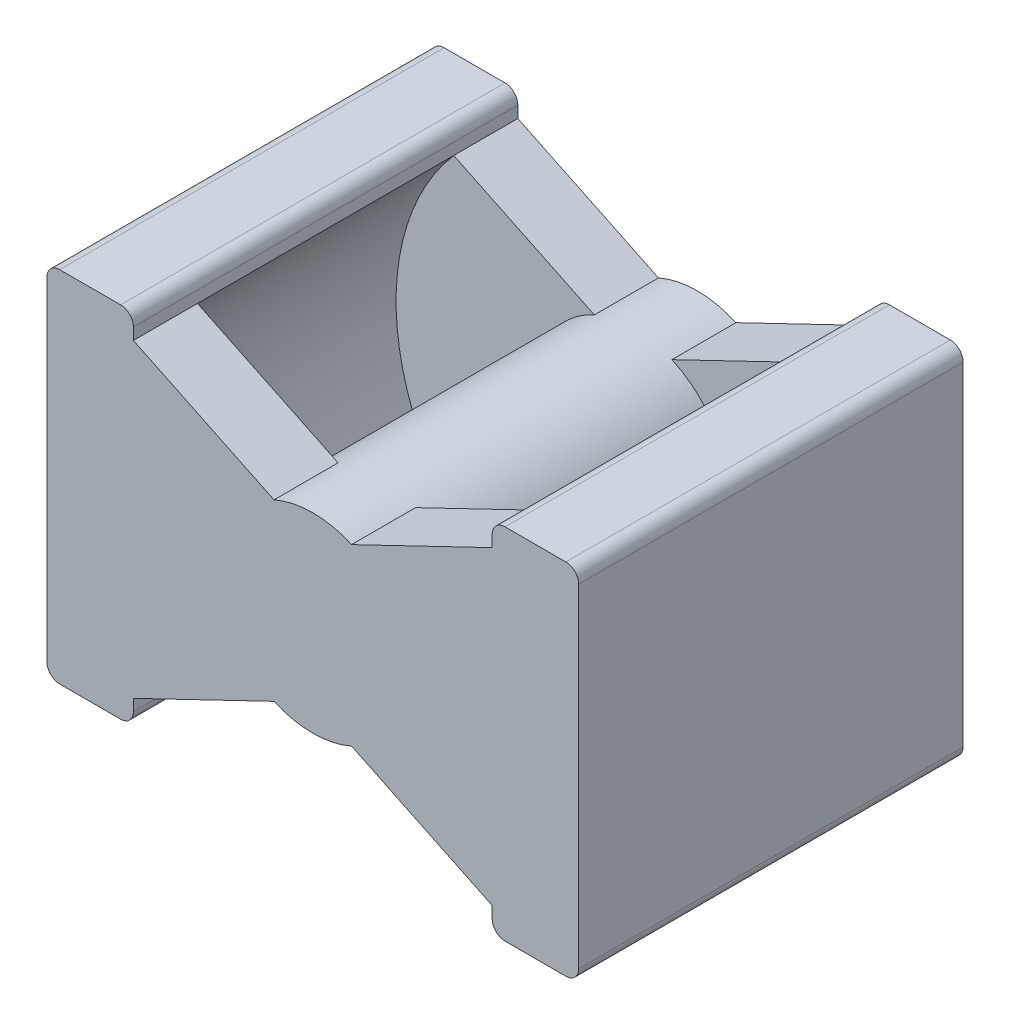
SolidWorks part; units mm, degrees
ref_plane "Ön Düzlem" through (0, 0, 0) normal (0, 0, 1) x (1, 0, 0)
ref_plane "Üst Düzlem" through (0, 0, 0) normal (0, 1, 0) x (1, 0, 0)
ref_plane "Sağ Düzlem" through (0, 0, 0) normal (1, 0, 0) x (0, 0, -1)
sketch "Sketch1" plane through (0, 0, 0) normal (0, 0, 1) x (1, 0, 0)
  line L0 (41.5, 14) -> (0, 14) construction
  line L1 (1, 0) -> (5.75, 0)
  line L2 (0, 1) -> (0, 27)
  line L3 (1, 28) -> (5.75, 28)
  line L4 (41.5, 1) -> (41.5, 27)
  line L5 (20.75, 28) -> (20.75, 0) construction
  line L6 (6.75, 27) -> (6.75, 26.0934)
  line L7 (34.75, 27) -> (34.75, 26.0934)
  line L12 (6.75, 26.0934) -> (17.725, 20.8082)
  line L13 (34.75, 26.0934) -> (23.775, 20.8082)
  line L14 (6.75, 1.9066) -> (17.725, 7.1918)
  line L15 (34.75, 1.9066) -> (23.775, 7.1918)
  line L16 (35.75, 28) -> (40.5, 28)
  line L17 (35.75, 0) -> (40.5, 0)
  line L18 (34.75, 1.9066) -> (34.75, 1)
  line L19 (34.75, 28) -> (34.75, 0) construction
  line L20 (6.75, 1.9066) -> (6.75, 1)
  line L21 (6.75, 28) -> (6.75, 0) construction
  arc A0 (17.725, 7.1918) -> (23.775, 7.1918) centre (20.75, 14) ccw
  arc A3 (23.775, 20.8082) -> (17.725, 20.8082) centre (20.75, 14) ccw
  arc A4 (34.75, 1) -> (35.75, 0) centre (35.75, 1) ccw
  arc A5 (6.75, 1) -> (5.75, 0) centre (5.75, 1) cw
  arc A6 (34.75, 27) -> (35.75, 28) centre (35.75, 27) cw
  arc A7 (6.75, 27) -> (5.75, 28) centre (5.75, 27) ccw
  arc A8 (40.5, 28) -> (41.5, 27) centre (40.5, 27) cw
  arc A9 (40.5, 0) -> (41.5, 1) centre (40.5, 1) ccw
  arc A10 (1, 0) -> (0, 1) centre (1, 1) cw
  arc A11 (0, 27) -> (1, 28) centre (1, 27) cw
  circle A12 centre (20.75, 14) radius 7.45
  point P38 (41.5, 0)
  point P41 (0, 0)
  point P44 (0, 28)
  dimension "D3" = 14.9
  dimension "D4" = 1
  dimension "D7" = 1
  dimension "D1" = 28
  dimension "D2" = 41.5
  dimension "D5" = 14
  dimension "D6" = 14
extrude "Boss-Extrude2" add sketch "Sketch1" along normal blind 30
sketch "Sketch4" plane through (0, 0, 0) normal (0, 0, -1) x (-1, 0, 0)
  circle A0 centre (-20.75, 14) radius 7.45
  circle A1 centre (-20.75, 14) radius 18.5
extrude "Cut-Extrude1" cut sketch "Sketch4" against normal blind 20 from offset 5
